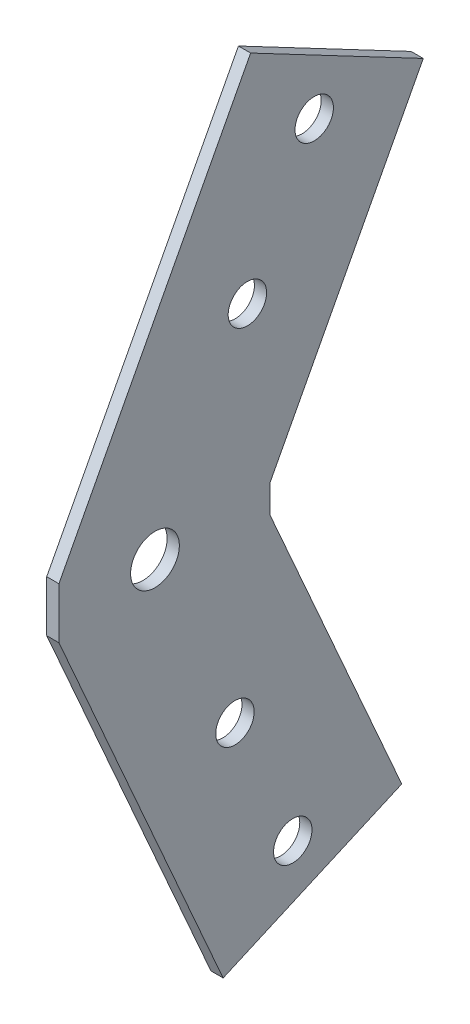
SolidWorks part; units mm, degrees
ref_plane "Front Plane" through (0, 0, 0) normal (1, 0, 0) x (0, 1, 0)
ref_plane "Top Plane" through (0, 0, 0) normal (0, 0, 1) x (0, 1, 0)
ref_plane "Right Plane" through (0, 0, 0) normal (0, 1, 0) x (-1, 0, 0)
sketch "Sketch1" plane through (0, 0, 0) normal (1, 0, 0) x (0, 1, 0)
  line L0 (0, 0) -> (-508, -224) construction
  line L1 (0, 0) -> (425, -224) construction
  line L2 (-92.9636, -40.9918) -> (-82.7156, -64.2327)
  line L3 (89.8802, -47.3721) -> (78.0371, -69.8422)
  line L4 (-92.9636, -40.9918) -> (-103.2116, -17.7509)
  line L5 (89.8802, -47.3721) -> (101.7232, -24.9021)
  line L6 (0, -68.1495) -> (0, 72.3635) construction
  line L7 (-82.7156, -64.2327) -> (-5.0807, -30)
  line L8 (78.0371, -69.8422) -> (2.4437, -30)
  line L9 (-103.2116, -17.7509) -> (-6.2586, 25)
  line L10 (101.7232, -24.9021) -> (7.0429, 25)
  line L11 (-5.0807, -30) -> (2.4437, -30)
  line L12 (-6.2586, 25) -> (7.0429, 25)
  circle A0 centre (0, 0) radius 6.35
  circle A1 centre (0, 0) radius 14.7875 construction
  circle A2 centre (-81.3431, -35.8678) radius 5
  circle A3 centre (-47.2138, -20.8187) radius 5
  circle A4 centre (78.6451, -41.4506) radius 5
  circle A5 centre (45.6478, -24.0591) radius 5
  point P6 (-92.9636, -40.9918)
  point P7 (89.8802, -47.3721)
  point P28 (0, 0)
  point P29 (0, 0)
  dimension "D5" = 12.7
  dimension "D6" = 29.575
  dimension "D7" = 101.6
  dimension "D13" = 30
  dimension "D14" = 25
  dimension "D15" = 10
  dimension "D16" = 10
  dimension "D17" = 10
  dimension "D18" = 10
  dimension "D1" = 508
  dimension "D2" = 425
  dimension "D3" = 224
  dimension "D4" = 224
  dimension "D8" = 101.6
  dimension "D9" = 25.4
  dimension "D10" = 25.4
  dimension "D11" = 25.4
  dimension "D12" = 25.4
  dimension "D19" = 12.7
  dimension "D20" = 12.7
  dimension "D21" = 50
  dimension "D22" = 50
extrude "Boss-Extrude1" add sketch "Sketch1" against normal blind 3.175 contours L12 L9 L4 L2 L7 L11 L8 L3 L5 L10 A1
